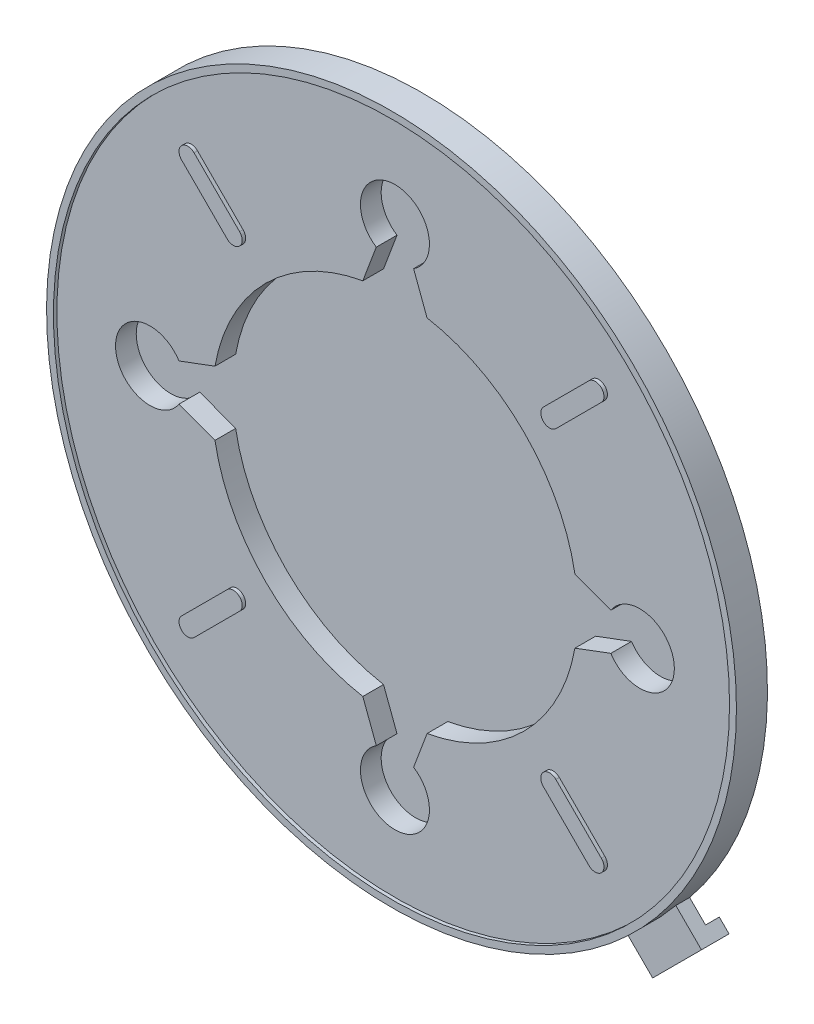
SolidWorks part; units mm, degrees
ref_plane "Alzado" through (0, 0, 0) normal (0, 0, 1) x (1, 0, 0)
ref_plane "Planta" through (0, 0, 0) normal (0, 1, 0) x (1, 0, 0)
ref_plane "Vista lateral" through (0, 0, 0) normal (1, 0, 0) x (0, 0, -1)
sketch "Croquis2" plane through (0, 0, -5) normal (0, 0, -1) x (-1, 0, 0)
  line L16 (-26.088, 4.6545) -> (-31.2933, 2.7025)
  line L17 (-31.2933, -2.7025) -> (-26.088, -4.6545)
  line L18 (-4.6545, -26.088) -> (-2.7025, -31.2933)
  line L19 (2.7025, -31.2933) -> (4.6545, -26.088)
  line L20 (26.088, -4.6545) -> (31.2933, -2.7025)
  line L21 (31.2933, 2.7025) -> (26.088, 4.6545)
  line L22 (4.6545, 26.088) -> (2.7025, 31.2933)
  line L23 (-2.7025, 31.2933) -> (-4.6545, 26.088)
  circle A0 centre (0, 0) radius 50
  arc A16 (-4.6545, 26.088) -> (-26.088, 4.6545) centre (0, 0) ccw
  arc A17 (-31.2933, 2.7025) -> (-31.2933, -2.7025) centre (-35.5, 0) ccw
  arc A18 (-26.088, -4.6545) -> (-4.6545, -26.088) centre (0, 0) ccw
  arc A19 (-2.7025, -31.2933) -> (2.7025, -31.2933) centre (0, -35.5) ccw
  arc A20 (4.6545, -26.088) -> (26.088, -4.6545) centre (0, 0) ccw
  arc A21 (31.2933, -2.7025) -> (31.2933, 2.7025) centre (35.5, 0) ccw
  arc A22 (26.088, 4.6545) -> (4.6545, 26.088) centre (0, 0) ccw
  arc A23 (2.7025, 31.2933) -> (-2.7025, 31.2933) centre (0, 35.5) ccw
  dimension "D2" = 100
extrude "Saliente-Extruir2" add sketch "Croquis2" against normal blind 3
sketch "Croquis3" plane through (0, 0, -5) normal (0, 0, -1) x (-1, 0, 0)
  circle A0 centre (0, 0) radius 50
extrude "Saliente-Extruir3" add sketch "Croquis3" along normal blind 1
sketch "Croquis4" plane through (0, 0, -6) normal (0, 0, -1) x (-1, 0, 0)
  circle A0 centre (0, 0) radius 18
  dimension "D1" = 36
extrude "Saliente-Extruir4" add sketch "Croquis4" along normal blind 6
sketch "Croquis5" plane through (0, 0, -2) normal (0, 0, 1) x (1, 0, 0)
  line L0 (0, 0) -> (35.3553, 35.3553) construction
  line L1 (29.5213, 29.5213) -> (22.9196, 22.9196) construction
  line L2 (30.4252, 28.6174) -> (23.8235, 22.0157)
  line L3 (28.6174, 30.4252) -> (22.0157, 23.8235)
  line L4 (29.5213, -29.5213) -> (22.9196, -22.9196) construction
  line L5 (28.6174, -30.4252) -> (22.0157, -23.8235)
  line L6 (30.4252, -28.6174) -> (23.8235, -22.0157)
  line L7 (-29.5213, -29.5213) -> (-22.9196, -22.9196) construction
  line L8 (-30.4252, -28.6174) -> (-23.8235, -22.0157)
  line L9 (-28.6174, -30.4252) -> (-22.0157, -23.8235)
  line L10 (-29.5213, 29.5213) -> (-22.9196, 22.9196) construction
  line L11 (-28.6174, 30.4252) -> (-22.0157, 23.8235)
  line L12 (-30.4252, 28.6174) -> (-23.8235, 22.0157)
  circle A0 centre (0, 0) radius 50
  circle A1 centre (0, 0) radius 49
  arc A2 (30.4252, 28.6174) -> (28.6174, 30.4252) centre (29.5213, 29.5213) ccw
  arc A3 (22.0157, 23.8235) -> (23.8235, 22.0157) centre (22.9196, 22.9196) ccw
  arc A4 (28.6174, -30.4252) -> (30.4252, -28.6174) centre (29.5213, -29.5213) ccw
  arc A5 (23.8235, -22.0157) -> (22.0157, -23.8235) centre (22.9196, -22.9196) ccw
  arc A6 (-30.4252, -28.6174) -> (-28.6174, -30.4252) centre (-29.5213, -29.5213) ccw
  arc A7 (-22.0157, -23.8235) -> (-23.8235, -22.0157) centre (-22.9196, -22.9196) ccw
  arc A8 (-28.6174, 30.4252) -> (-30.4252, 28.6174) centre (-29.5213, 29.5213) ccw
  arc A9 (-23.8235, 22.0157) -> (-22.0157, 23.8235) centre (-22.9196, 22.9196) ccw
  point P8 (26.2205, 26.2205)
  point P18 (26.2205, -26.2205)
  point P25 (-26.2205, -26.2205)
  point P32 (-26.2205, 26.2205)
  point P37 (0, 0)
  circle M18 centre (0, 0) radius 50
  dimension "D1" = 1
  dimension "D2" = 4
extrude "Saliente-Extruir5" add sketch "Croquis5" along normal blind 0.5 contours L12 A9 L11 A8 | A1 M18 | L6 A5 L5 A4 | L9 A7 L8 A6 | L3 A3 L2 A2
sketch "Croquis6" plane through (0, 0, -6) normal (0, 0, -1) x (-1, 0, 0)
  line L0 (0, 0) -> (-35.3553, -35.3553) construction
  line L1 (-38.8909, -31.8198) -> (-31.8198, -38.8909) construction
  line L2 (-30.3182, -37.3893) -> (-35.3553, -42.4264)
  line L3 (-38.8909, -31.8198) -> (-37.3893, -30.3182)
  line L4 (-38.8909, -31.8198) -> (-42.4264, -35.3553)
  line L5 (-35.3553, -42.4264) -> (-42.4264, -35.3553)
  line L6 (-37.3893, -30.3182) -> (-30.3182, -37.3893)
  circle A0 centre (0, 0) radius 50 construction
  dimension "D1" = 10
  dimension "D2" = 5
extrude "Saliente-Extruir6" add sketch "Croquis6" against normal blind 2
sketch "Croquis7" plane through (0, 0, -6) normal (0, 0, -1) x (-1, 0, 0)
  line L0 (-42.4264, -35.3553) -> (-41.0147, -33.9436)
  line L1 (-38.7137, -31.6426) -> (-42.4264, -35.3553) construction
  line L2 (-41.0147, -33.9436) -> (-33.9436, -41.0147)
  line L3 (-35.3553, -42.4264) -> (-31.6426, -38.7137) construction
  line L4 (-33.9436, -41.0147) -> (-35.3553, -42.4264)
  line L5 (-35.3553, -42.4264) -> (-42.4264, -35.3553)
extrude "Saliente-Extruir7" add sketch "Croquis7" along normal blind 2
sketch "Croquis8" plane through (0, 0, -2) normal (0, 0, 1) x (1, 0, 0)
  line L0 (0, 0) -> (50.2289, -50.2289) construction
